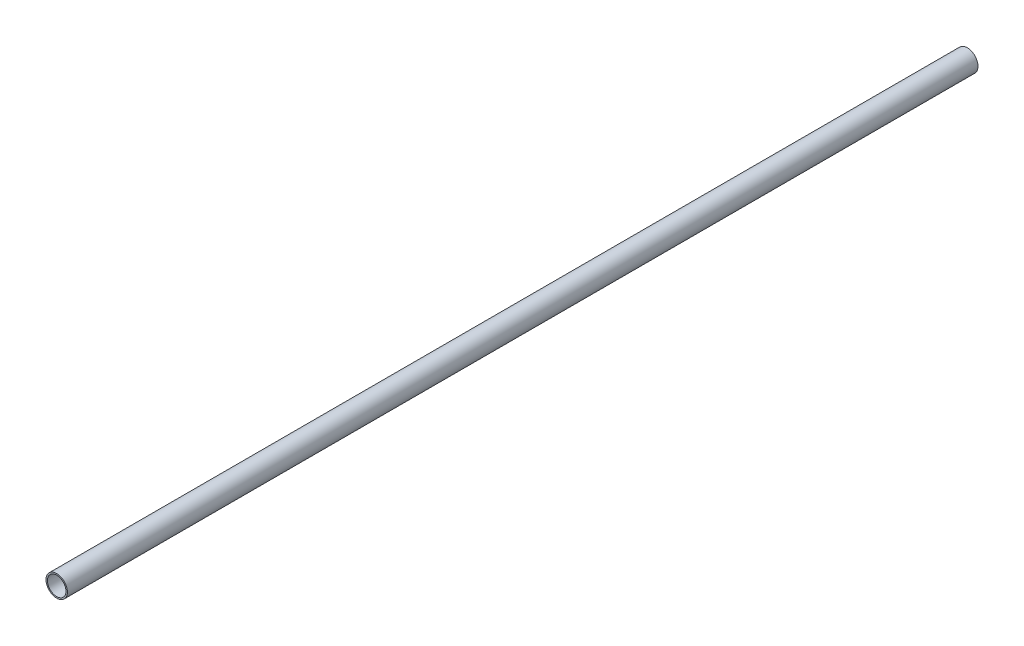
SolidWorks part; units mm, degrees
material "CARBON FIBERR"
ref_plane "Front" through (0, 0, 0) normal (0, 0, 1) x (1, 0, 0)
ref_plane "Top" through (0, 0, 0) normal (0, 1, 0) x (1, 0, 0)
ref_plane "Right" through (0, 0, 0) normal (1, 0, 0) x (0, 0, -1)
sketch "Sketch1" plane through (0, 0, 0) normal (0, 0, 1) x (1, 0, 0)
  circle A0 centre (0, 0) radius 10.3505
  circle A1 centre (0, 0) radius 11.938
  dimension "D1" = 23.876
  dimension "D2" = 1.5875
extrude "Boss-Extrude1" add sketch "Sketch1" against normal blind 1016
equation "\"Wing Start\" = 9.5in"
equation "\"Wing Twist\" = 1deg"
equation "\"Fuse Twist\" = 2deg"
equation "\"Fuse Chord\" = 31.6in"
equation "\"Straight Chord\" = 21.07in"
equation "\"Tip Chord\" = 9.36in"
equation "\"D1@Boss-Extrude1\"= \"Tail Boom Length\""
